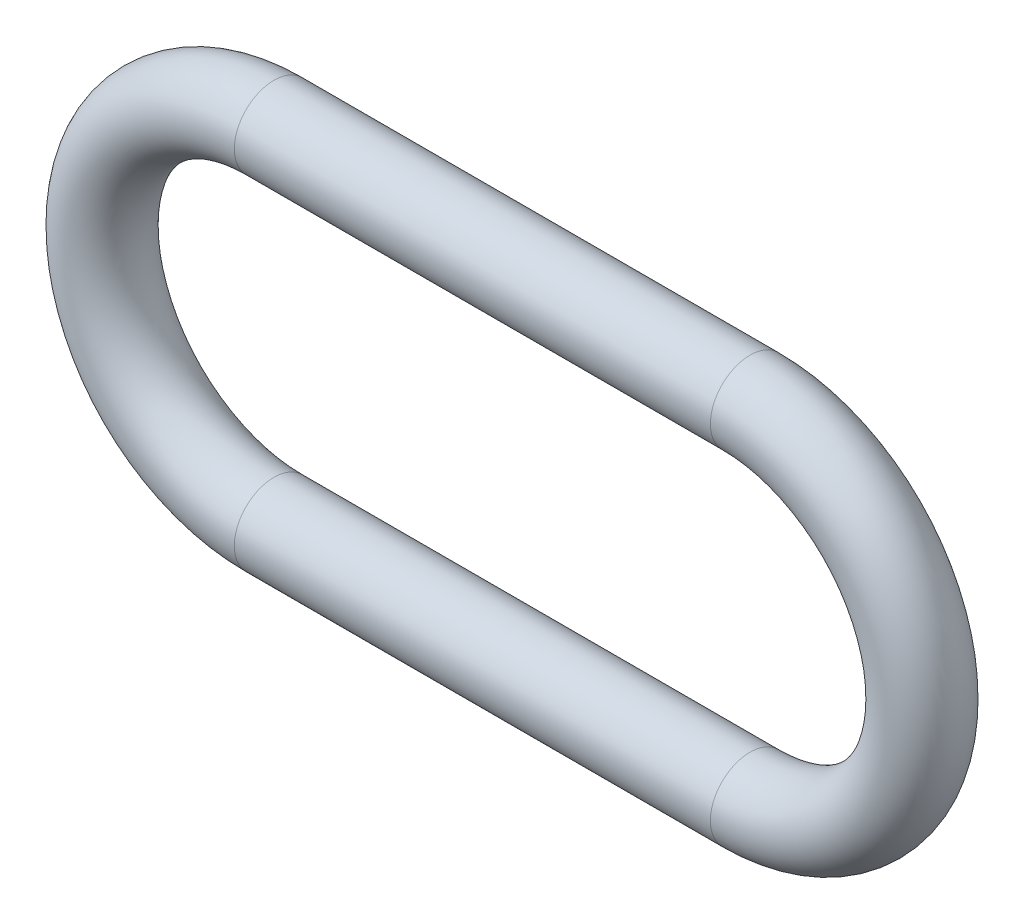
SolidWorks part; units mm, degrees
ref_plane "Plan de face" through (0, 0, 0) normal (0, 0, 1) x (1, 0, 0)
ref_plane "Plan de dessus" through (0, 0, 0) normal (0, 1, 0) x (1, 0, 0)
ref_plane "Plan de droite" through (0, 0, 0) normal (1, 0, 0) x (0, 0, -1)
sketch "Esquisse1" plane through (0, 0, 0) normal (0, 0, 1) x (1, 0, 0)
  line L0 (0, 6.5) -> (18, 6.5)
  line L1 (18, -6.5) -> (0, -6.5)
  line L2 (0, 6.5) -> (0, -6.5) construction
  line L3 (18, 6.5) -> (18, -6.5) construction
  circle A0 centre (0, 0) radius 5 construction
  circle A1 centre (18, 0) radius 5 construction
  arc A4 (18, 6.5) -> (18, -6.5) centre (18, 0) cw
  arc A5 (0, 6.5) -> (0, -6.5) centre (0, 0) ccw
  dimension "D1" = 10
  dimension "D2" = 10
  dimension "D4" = 1.5
  dimension "D3" = 18
sketch "Esquisse2" plane through (0, 0, 0) normal (1, 0, 0) x (0, 0, -1)
  circle A0 centre (0, 6.5) radius 1.5
  dimension "D1" = 3
sweep "Balayage1" add profiles "Esquisse2" path "Esquisse1"
